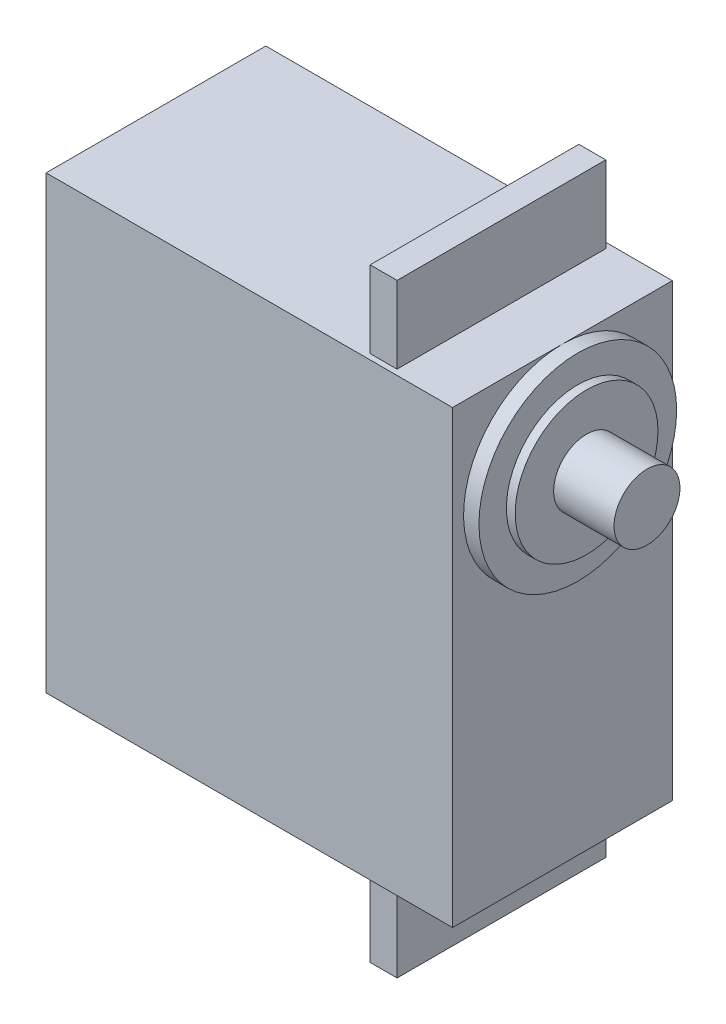
SolidWorks part; units mm, degrees
ref_plane "前基準面" through (0, 0, 0) normal (0, 0, 1) x (1, 0, 0)
ref_plane "上基準面" through (0, 0, 0) normal (0, 1, 0) x (1, 0, 0)
ref_plane "右基準面" through (0, 0, 0) normal (1, 0, 0) x (0, 0, -1)
sketch "草圖1" plane through (0, 0, 0) normal (1, 0, 0) x (0, 0, -1)
  line L1 (-11.083, 18.2146) -> (8.917, 18.2146)
  line L2 (-11.083, 18.2146) -> (-11.083, -22.7854)
  line L3 (-11.083, -22.7854) -> (8.917, -22.7854)
  line L4 (8.917, 18.2146) -> (8.917, -22.7854)
  dimension "D1" = 20
  dimension "D2" = 41
extrude "填料-伸長1" add sketch "草圖1" along normal blind 37 contours L2 L1 L4 L3
sketch "草圖2" plane through (0, 18.2146, 0) normal (0, 1, 0) x (1, 0, 0)
  line L0 (37, -11.083) -> (0, -11.083) construction
  line L1 (29, 8.417) -> (31.45, 8.417)
  line L2 (29, 8.417) -> (29, -10.583)
  line L3 (29, -10.583) -> (31.45, -10.583)
  line L4 (31.45, 8.417) -> (31.45, -10.583)
  line L6 (37, -11.083) -> (37, 8.917) construction
  dimension "D1" = 19
  dimension "D2" = 0.5
  dimension "D3" = 8
  dimension "D4" = 2.45
extrude "填料-伸長2" add sketch "草圖2" along normal blind 7 contours L2 L1 L4 L3
sketch "草圖3" plane through (0, -22.7854, 0) normal (0, -1, 0) x (1, 0, 0)
  line L0 (37, -8.917) -> (0, -8.917) construction
  line L1 (31.45, -8.417) -> (29, -8.417)
  line L2 (31.45, -8.417) -> (31.45, 10.583)
  line L3 (31.45, 10.583) -> (29, 10.583)
  line L4 (29, -8.417) -> (29, 10.583)
  line L5 (37, 11.083) -> (37, -8.917) construction
  dimension "D1" = 19
  dimension "D2" = 0.5
  dimension "D3" = 2.45
  dimension "D4" = 8
extrude "填料-伸長3" add sketch "草圖3" along normal blind 7
sketch "草圖4" plane through (37, 0, 0) normal (1, 0, 0) x (0, 0, -1)
  line L0 (-11.083, 18.2146) -> (8.917, 18.2146) construction
  line L1 (8.917, 18.2146) -> (8.917, -22.7854) construction
  circle A0 centre (-1.083, 9.2146) radius 3
  dimension "D1" = 6
  dimension "D2" = 9
  dimension "D3" = 10
extrude "填料-伸長4" add sketch "草圖4" along normal blind 7.7
sketch "草圖5" plane through (37, 0, 0) normal (1, 0, 0) x (0, 0, -1)
  circle A0 centre (-1.083, 9.2146) radius 9
  dimension "D1" = 18
extrude "填料-伸長5" add sketch "草圖5" along normal blind 1.4
sketch "草圖7" plane through (38.4, 0, 0) normal (1, 0, 0) x (0, 0, -1)
  circle A0 centre (-1.083, 9.2146) radius 6.5
  dimension "D1" = 13
extrude "填料-伸長6" add sketch "草圖7" along normal blind 0.8
